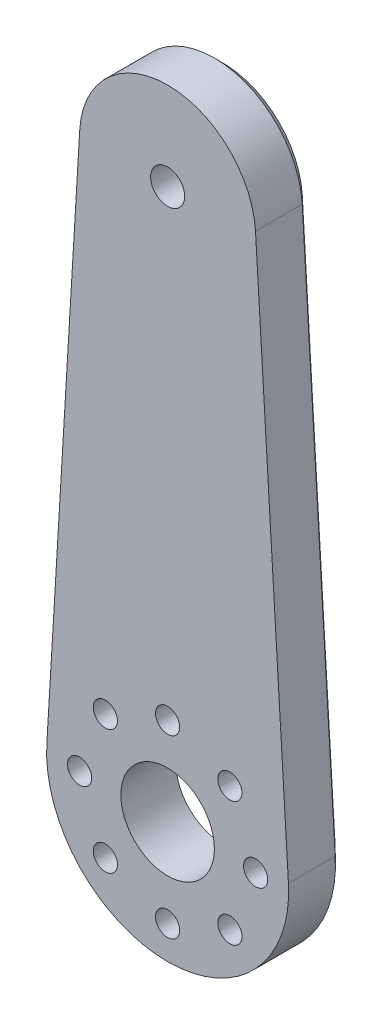
SolidWorks part; units mm, degrees
ref_plane "Front Plane" through (0, 0, 0) normal (0, 0, 1) x (1, 0, 0)
ref_plane "Top Plane" through (0, 0, 0) normal (0, 1, 0) x (1, 0, 0)
ref_plane "Right Plane" through (0, 0, 0) normal (1, 0, 0) x (0, 0, -1)
sketch "Sketch1" plane through (0, 0, 0) normal (0, 0, 1) x (1, 0, 0)
  line L0 (-23.1239, 31.3961) -> (-26.1185, -18.4239)
  line L3 (-7.1527, 31.3961) -> (-4.1581, -18.4239)
  line L4 (-15.1383, 0.8298) -> (-15.1383, 20.8298) construction
  line L5 (-14.787, -19.0839) -> (49985.213, -19.0839) construction
  circle A2 centre (-15.1383, 30.9161) radius 1.55
  circle A3 centre (-15.1383, -19.0839) radius 4.25
  arc A5 (-7.1527, 31.3961) -> (-23.1239, 31.3961) centre (-15.1383, 30.9161) ccw
  arc A6 (-26.1185, -18.4239) -> (-4.1581, -18.4239) centre (-15.1383, -19.0839) ccw
  circle A7 centre (-15.0314, -20.0888) radius 11 construction
  circle A8 centre (-7.1383, -19.0839) radius 1.1
  circle A9 centre (-9.4814, -24.7408) radius 1.1
  circle A10 centre (-15.1383, -27.0839) radius 1.1
  circle A11 centre (-20.7951, -24.7408) radius 1.1
  circle A12 centre (-23.1383, -19.0839) radius 1.1
  circle A13 centre (-20.7951, -13.427) radius 1.1
  circle A14 centre (-15.1383, -11.0839) radius 1.1
  circle A15 centre (-9.4814, -13.427) radius 1.1
  point P30 (-15.1383, -19.0839)
  dimension "D1" = 3.1
  dimension "D3" = 50
  dimension "D4" = 11
  dimension "D2" = 8
  dimension "D5" = 8.5
  dimension "D6" = 2.2
  dimension "D7" = 8
  dimension "D8" = 8
extrude "Boss-Extrude1" add sketch "Sketch1" along normal blind 5
sketch "Sketch2" plane through (0, 0, 5) normal (0, 0, 1) x (1, 0, 0)
  circle A0 centre (-15.1383, -19.0839) radius 11.5
  dimension "D1" = 23
extrude "Cut-Extrude1" [suppressed] cut sketch "Sketch2" against normal blind 1.75
sketch "Sketch3" plane through (0, 0, 0) normal (0, 0, 1) x (1, 0, 0)
  line L1 (-13.5506, 28.1661) -> (-11.9629, 30.9161)
  line L2 (-11.9629, 30.9161) -> (-13.5506, 33.6661)
  line L3 (-13.5506, 33.6661) -> (-16.726, 33.6661)
  line L4 (-16.726, 33.6661) -> (-18.3137, 30.9161)
  line L5 (-18.3137, 30.9161) -> (-16.726, 28.1661)
  line L6 (-16.726, 28.1661) -> (-13.5506, 28.1661)
  circle A0 centre (-15.1383, 30.9161) radius 2.75 construction
  dimension "D1" = 5.5
extrude "Cut-Extrude2" cut sketch "Sketch3" along normal blind 2
sketch "Sketch5" plane through (0, 0, 5) normal (0, 0, 1) x (1, 0, 0)
  circle A2 centre (-14.8897, 3.8764) radius 1.55
  circle A3 centre (-14.8897, 3.8764) radius 8
extrude "Boss-Extrude2" [suppressed] add sketch "Sketch5" along normal blind 3
fillet "Fillet1" [suppressed] radius 1
sketch "Sketch4" plane through (0, 0, 0) normal (0, 0, -1) x (-1, 0, 0)
  circle A0 centre (23.1383, -19.0839) radius 1.75
  circle A1 centre (20.7951, -24.7408) radius 1.75
  circle A2 centre (15.1383, -27.0839) radius 1.75
  circle A3 centre (9.4814, -24.7408) radius 1.75
  circle A4 centre (7.1383, -19.0839) radius 1.75
  circle A5 centre (9.4814, -13.427) radius 1.75
  circle A6 centre (15.1383, -11.0839) radius 1.75
  circle A7 centre (20.7951, -13.427) radius 1.75
  circle A10 centre (15.1383, -19.0839) radius 4.25 construction
  point P20 (15.1383, -19.0839)
  dimension "D1" = 3.5
extrude "Cut-Extrude3" cut sketch "Sketch4" against normal blind 2.25
chamfer "Chaflán1" distance 0.75 angle 45 4 edges at (-24.6212, 6.4861, 0) (-15.1383, -30.0839, 0) (-15.1383, 38.9161, 0) (-5.6554, 6.4861, 0)
